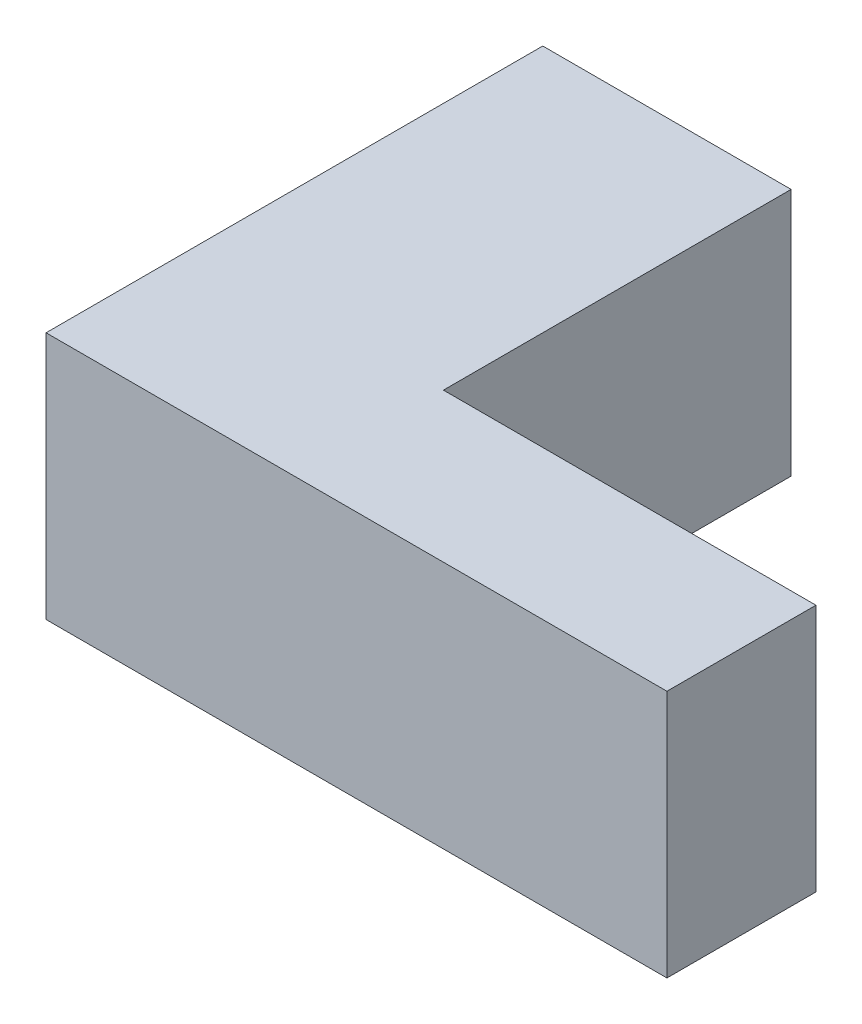
SolidWorks part; units mm, degrees
ref_plane "Piano frontale" through (0, 0, 0) normal (0, 0, 1) x (1, 0, 0)
ref_plane "Piano superiore" through (0, 0, 0) normal (0, 1, 0) x (1, 0, 0)
ref_plane "Piano destro" through (0, 0, 0) normal (1, 0, 0) x (0, 0, -1)
sketch "Schizzo1" plane through (0, 0, 0) normal (0, 0, 1) x (1, 0, 0)
  line L1 (5, -5) -> (-5, -5)
  line L2 (5, -5) -> (5, 5)
  line L3 (5, 5) -> (-5, 5)
  line L4 (-5, -5) -> (-5, 5)
  line L5 (5, -5) -> (-5, 5) construction
  line L6 (5, 5) -> (-5, -5) construction
  point P0 (0, 0)
  dimension "D1" = 10
  dimension "D2" = 10
extrude "Estrusione-Estrusione1" add sketch "Schizzo1" along normal blind 20
sketch "Schizzo2" plane through (0, 0, 0) normal (0, 1, 0) x (1, 0, 0)
  line L1 (5, -20) -> (20, -20)
  line L2 (5, -20) -> (5, -14)
  line L3 (5, -14) -> (20, -14)
  line L4 (20, -20) -> (20, -14)
  dimension "D1" = 6
  dimension "D2" = 15
extrude "Estrusione-Estrusione2" add sketch "Schizzo2" along normal mid plane 10
